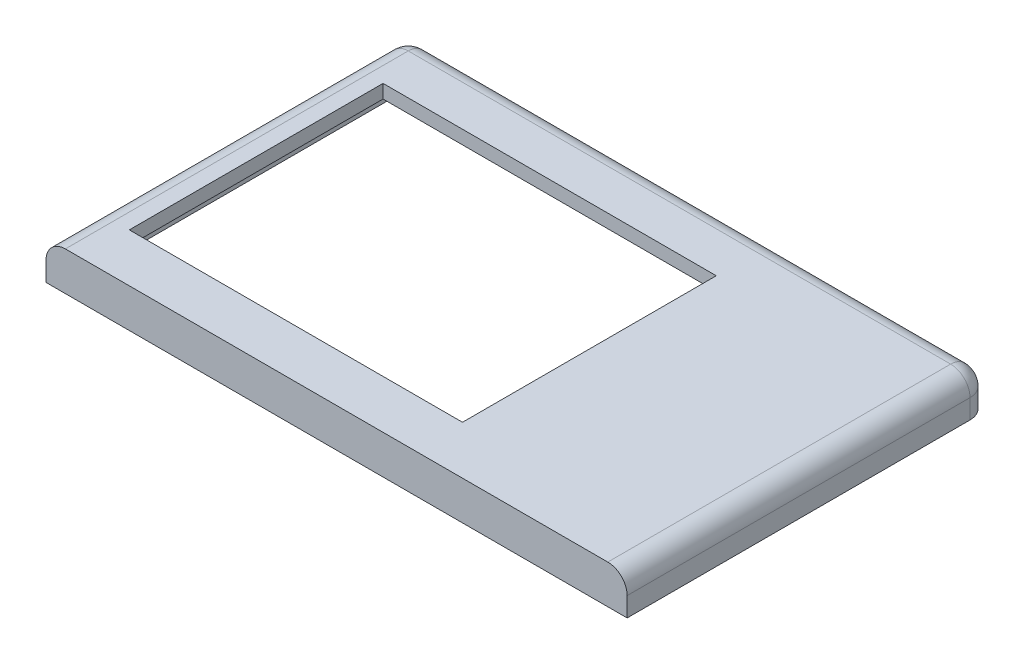
SolidWorks part; units mm, degrees
ref_plane "Front Plane" through (0, 0, 0) normal (0, 0, 1) x (1, 0, 0)
ref_plane "Top Plane" through (0, 0, 0) normal (0, 1, 0) x (1, 0, 0)
ref_plane "Right Plane" through (0, 0, 0) normal (1, 0, 0) x (0, 0, -1)
sketch "Sketch1" plane through (0, 0, 0) normal (0, 1, 0) x (1, 0, 0)
  line L1 (-78.2627, 31.9813) -> (221.7373, 31.9813)
  line L2 (-78.2627, 31.9813) -> (-78.2627, -155.0187)
  line L3 (-78.2627, -155.0187) -> (221.7373, -155.0187)
  line L4 (221.7373, 31.9813) -> (221.7373, -155.0187)
  dimension "D1" = 187
  dimension "D2" = 300
extrude "Boss-Extrude1" add sketch "Sketch1" along normal blind 20 contours L2 L1 L4 L3
fillet "Fillet1" radius 10 1 edges at (-78.2627, 20, 61.5187)
fillet "Fillet2" radius 10 1 edges at (221.7373, 20, 61.5187)
sketch "Sketch2" plane through (0, 20, 0) normal (0, 1, 0) x (1, 0, 0)
  line L0 (-68.2627, 31.9813) -> (-68.2627, -155.0187) construction
  line L1 (-60.2627, 0.9813) -> (111.7373, 0.9813)
  line L2 (-60.2627, 0.9813) -> (-60.2627, -130.0187)
  line L3 (-60.2627, -130.0187) -> (111.7373, -130.0187)
  line L4 (111.7373, 0.9813) -> (111.7373, -130.0187)
  line L5 (-68.2627, 31.9813) -> (211.7373, 31.9813) construction
  line L7 (-68.2627, -155.0187) -> (211.7373, -155.0187) construction
  line L8 (211.7373, -155.0187) -> (211.7373, 31.9813) construction
  dimension "D1" = 8
  dimension "D2" = 31
  dimension "D3" = 100
  dimension "D4" = 25
  dimension "D5" = 172
shell "Shell2" thickness 7
extrude "Cut-Extrude2" cut sketch "Sketch2" against normal blind 7 contours L1 L4 L3 L2
fillet "Fillet3" radius 10 5 edges at (221.7373, 5, -31.9813) (218.8084, 17.0711, -31.9813) (71.7373, 20, -31.9813) (-75.3337, 17.0711, -31.9813) (-78.2627, 5, -31.9813)
